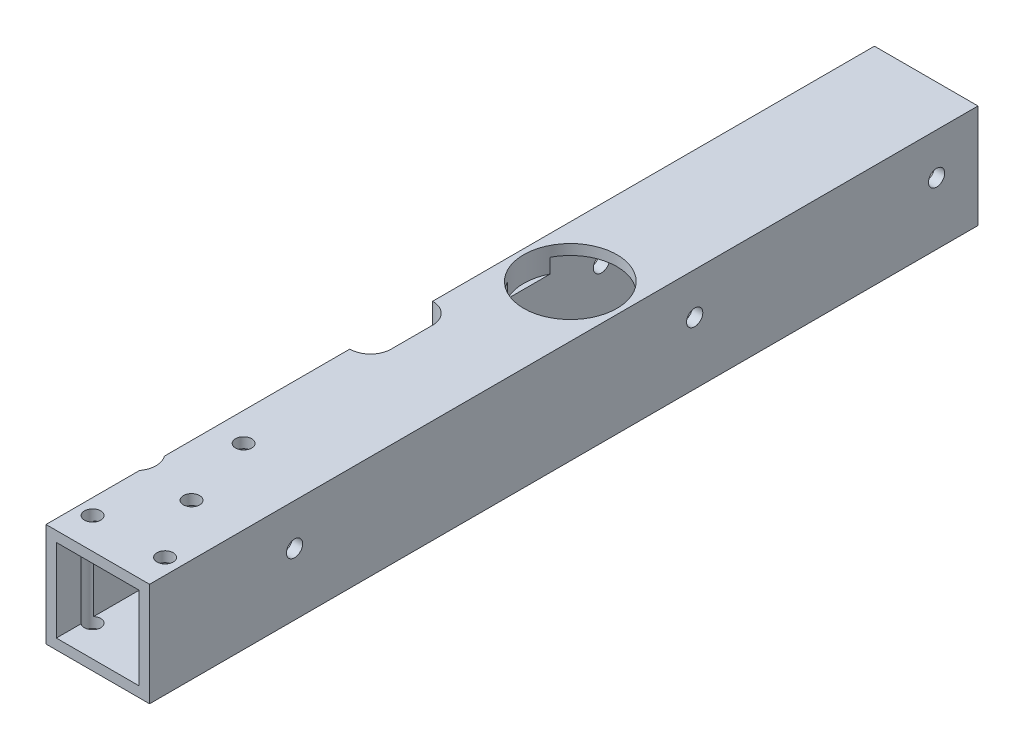
SolidWorks part; units mm, degrees
material "6061 Alloy"
ref_plane "Front Plane" through (0, 0, 0) normal (0, 0, 1) x (1, 0, 0)
ref_plane "Top Plane" through (0, 0, 0) normal (0, 1, 0) x (1, 0, 0)
ref_plane "Right Plane" through (0, 0, 0) normal (1, 0, 0) x (0, 0, -1)
sketch "Sketch1" plane through (0, 0, 0) normal (0, 0, 1) x (1, 0, 0)
  line L0 (-12.7, 12.7) -> (12.7, 12.7)
  line L2 (-15.875, 15.875) -> (15.875, 15.875)
  line L3 (-15.875, 15.875) -> (-15.875, -15.875)
  line L4 (-15.875, -15.875) -> (15.875, -15.875)
  line L5 (15.875, 15.875) -> (15.875, -15.875)
  line L10 (12.7, 12.7) -> (12.7, -12.7)
  line L11 (-12.7, -12.7) -> (12.7, -12.7)
  line L12 (-12.7, 12.7) -> (-12.7, -12.7)
  point P12 (0, 15.875)
  point P14 (15.875, 0)
  dimension "Wall Thickness" = 3.175
  dimension "Outside Width" = 31.75
  dimension "Outside Height" = 31.75
  dimension "Inside Height" = 25.4
  dimension "Inside Width" = 25.4
sketch "Sketch2" plane through (0, 0, 0) normal (1, 0, 0) x (0, 0, -1)
  line L0 (127, 0) -> (-127, 0)
  point P4 (0, 0)
  point P7 (-127, 0)
  point P10 (127, 0)
  dimension "Length" = 254
sketch "Sketch3" plane through (0, 0, 0) normal (0, 0, 1) x (1, 0, 0)
  line L21 (15.875, 15.875) -> (-15.875, 15.875)
  line L22 (15.875, -15.875) -> (15.875, 15.875)
  line L23 (-15.875, -15.875) -> (15.875, -15.875)
  line L24 (-15.875, 15.875) -> (-15.875, -15.875)
  line L25 (15.875, 15.875) -> (-15.875, 15.875)
  line L26 (15.875, -15.875) -> (15.875, 15.875)
  line L27 (-15.875, -15.875) -> (15.875, -15.875)
  line L28 (-15.875, 15.875) -> (-15.875, -15.875)
  line L29 (12.7, 12.7) -> (-12.7, 12.7)
  line L30 (12.7, -12.7) -> (12.7, 12.7)
  line L31 (-12.7, -12.7) -> (12.7, -12.7)
  line L32 (-12.7, 12.7) -> (-12.7, -12.7)
  line L33 (12.7, 12.7) -> (-12.7, 12.7)
  line L34 (12.7, -12.7) -> (12.7, 12.7)
  line L35 (-12.7, -12.7) -> (12.7, -12.7)
  line L36 (-12.7, 12.7) -> (-12.7, -12.7)
  dimension "D1" = 0
  dimension "D2" = 0
extrude "Boss-Extrude1" add sketch "Sketch3" along normal up to vertex (127 mm away) and the other way up to vertex (127 mm away) up to point (0, 0, 127) other way up to point (0, 0, -127)
sketch "Drawing Reference" plane through (0, 0, 0) normal (1, 0, 0) x (0, 0, -1)
  line L0 (-127, 0) -> (127, 0) construction
  line L1 (0, -15.875) -> (0, 15.875) construction
  line L2 (-127, -15.875) -> (127, -15.875) construction
  line L5 (-127, 15.875) -> (127, 15.875) construction
  point P7 (-104.14, 0)
  point P8 (104.14, 0)
  dimension "D1" = 22.86
sketch "Sketch4" plane through (0, 15.875, 0) normal (0, 1, 0) x (1, 0, 0)
  line L0 (0, -127) -> (0, -117.475) construction
  line L1 (15.875, -127) -> (-15.875, -127) construction
  line L2 (0, -117.475) -> (11.1125, -117.475) construction
  line L3 (0, -117.475) -> (-11.1125, -117.475) construction
  line L4 (0, -117.475) -> (0, 17.8816) construction
  line L5 (0, -117.475) -> (0, -98.2472) construction
  point P5 (-7.1119, -75.1713)
  dimension "D1" = 135.3566
  dimension "D2" = 22.225
  dimension "D3" = 9.525
hole_wizard "#10 Clearance Hole1" positions "Sketch5" profile "Sketch6" hole size "#10" standard "ANSI Inch" end condition through all
sketch "Sketch5" plane through (0, 15.875, 0) normal (0, 1, 0) x (1, 0, 0)
  point P0 (-11.1125, -117.475)
  point P3 (11.1125, -117.475)
  point P7 (0, -98.2472)
  point P10 (-7.1119, -75.1713)
sketch "Sketch6" plane through (-11.1125, 15.875, 117.475) normal (1, 0, 0) x (0, 0, 1)
  line L0 (0, 0) -> (0, 31.75)
  line L1 (0, 31.75) -> (2.4892, 31.75)
  line L2 (2.4892, 31.75) -> (2.4892, 0)
  line L5 (2.4892, 0) -> (0, 0)
  line L11 (0, -6.35) -> (0, 107.95) construction
  dimension "Thru Hole Dia." = 4.9784
  dimension "Thru Hole Depth" = 31.75
sketch "Sketch7" plane through (0, 15.875, 0) normal (0, 1, 0) x (1, 0, 0)
  circle A0 centre (0, 17.8816) radius 14.2875
  dimension "D1" = 28.575
extrude "Cut-Extrude1" cut sketch "Sketch7" against normal blind 7.62
sketch "Sketch8" plane through (0, -15.875, 0) normal (0, -1, 0) x (1, 0, 0)
  circle A0 centre (0, -17.8816) radius 14.2875
  dimension "D1" = 28.575
extrude "Cut-Extrude2" cut sketch "Sketch8" against normal blind 7.62
sketch "Sketch9" plane through (0, -15.875, 0) normal (0, -1, 0) x (1, 0, 0)
  line L0 (-20.5727, 87.7258) -> (-42.1132, 74.2659) construction
  line L1 (-42.1132, 74.2659) -> (-15.875, 32.276) construction
  line L2 (-15.875, 127) -> (-15.875, -127) construction
  line L3 (-15.875, 32.276) -> (-9.099, 21.4322) construction
  line L4 (-15.875, 32.276) -> (-15.875, 27.5135) construction
  line L5 (-15.875, 27.5135) -> (-15.875, 14.8135) construction
  line L6 (-9.525, 27.5135) -> (-9.525, 14.8135)
  line L7 (-15.875, 8.4635) -> (-15.875, 33.8635)
  circle A0 centre (-15.875, 27.5135) radius 6.35 construction
  circle A1 centre (-15.875, 14.8135) radius 6.35 construction
  arc A2 (-15.875, 33.8635) -> (-9.525, 27.5135) centre (-15.875, 27.5135) cw
  arc A3 (-15.875, 8.4635) -> (-9.525, 14.8135) centre (-15.875, 14.8135) ccw
  dimension "D1" = 12.7
  dimension "D2" = 4.7625
extrude "Cut-Extrude3" cut sketch "Sketch9" against normal through all
sketch "Sketch10" plane through (15.875, 0, 0) normal (1, 0, 0) x (0, 0, -1)
  line L0 (-127, 3.175) -> (-82.55, 3.175) construction
  line L2 (-82.55, 3.175) -> (114.3, 3.175) construction
  line L3 (-127, -15.875) -> (-127, 3.175) construction
  line L4 (52.832, 3.175) -> (40.132, 3.175) construction
  line L5 (52.832, 434.0225) -> (52.832, -10.4775) construction
  dimension "D1" = 44.45
  dimension "D2" = 19.05
  dimension "D3" = 12.7
hole_wizard "#10 Clearance Hole2" positions "Sketch11" profile "Sketch12" hole size "#10" standard "ANSI Inch" end condition through all
sketch "Sketch11" plane through (15.875, 0, 0) normal (1, 0, 0) x (0, 0, -1)
  point P4 (-82.55, 3.175)
  point P7 (114.3, 3.175)
  point P12 (40.132, 3.175)
sketch "Sketch12" plane through (15.875, 3.175, 82.55) normal (0, 1, 0) x (0, 0, -1)
  line L0 (0, 0) -> (0, 31.75)
  line L1 (0, 31.75) -> (2.4892, 31.75)
  line L2 (2.4892, 31.75) -> (2.4892, 0)
  line L5 (2.4892, 0) -> (0, 0)
  line L11 (0, -6.35) -> (0, 107.95) construction
  dimension "Thru Hole Dia." = 4.9784
  dimension "Thru Hole Depth" = 31.75
sketch "Sketch13" plane through (0, -15.875, 0) normal (0, -1, 0) x (1, 0, 0)
  line L0 (-20.955, 94.5257) -> (-15.875, 94.5257) construction
  line L4 (-15.875, 127) -> (-15.875, 33.8635) construction
  circle A1 centre (-20.955, 94.5257) radius 6.35
  dimension "D1" = 5.08
extrude "Cut-Extrude4" cut sketch "Sketch13" against normal through all
equation "\"D1@Drawing Reference\"=\"Outside Width@Sketch1\" * 0.72"
